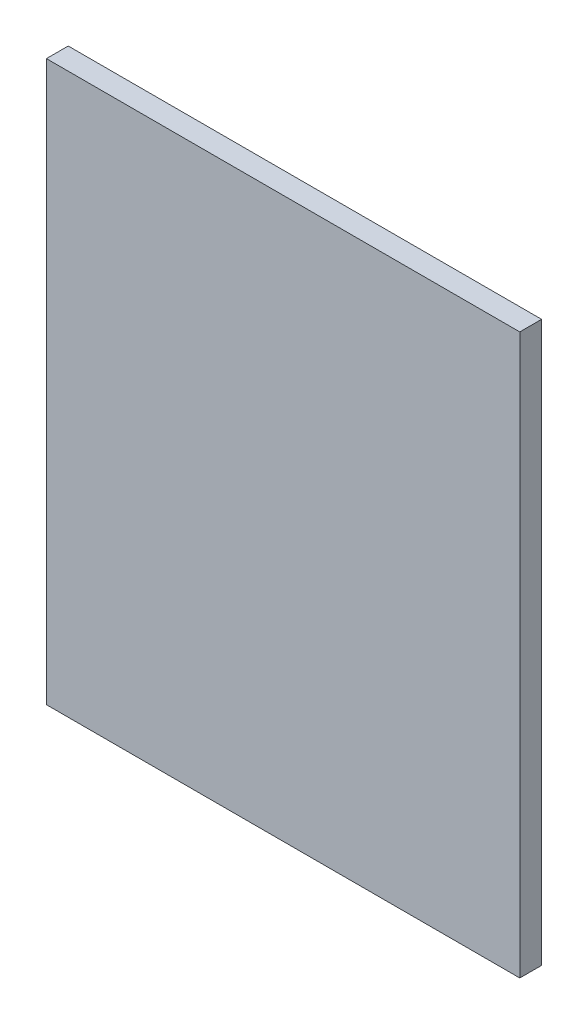
SolidWorks part; units mm, degrees
ref_plane "Front Plane" through (0, 0, 0) normal (0, 0, 1) x (1, 0, 0)
ref_plane "Top Plane" through (0, 0, 0) normal (0, 1, 0) x (1, 0, 0)
ref_plane "Right Plane" through (0, 0, 0) normal (1, 0, 0) x (0, 0, -1)
sketch "Sketch2" plane through (0, 0, 0) normal (0, 0, 1) x (1, 0, 0)
  line L16 (-88.9457, -6.4) -> (-88.9457, -1.9)
  line L17 (-88.9457, -1.9) -> (-93.6457, -1.9)
  line L18 (-93.6457, -1.9) -> (-93.6457, -44.6)
  line L19 (-93.6457, -44.6) -> (-26.1457, -44.6)
  line L20 (-26.1457, -44.6) -> (-26.1457, -1.9)
  line L21 (-26.1457, -1.9) -> (-70.1457, -1.9)
  line L22 (-70.1457, -1.9) -> (-70.1457, -6.4)
  line L23 (-70.1457, -6.4) -> (-88.9457, -6.4)
  line L24 (-88.9457, -6.4) -> (-88.9457, -1.9)
  line L25 (-88.9457, -1.9) -> (-93.6457, -1.9)
  line L26 (-93.6457, -1.9) -> (-93.6457, -44.6)
  line L27 (-93.6457, -44.6) -> (-26.1457, -44.6)
  line L28 (-26.1457, -44.6) -> (-26.1457, -1.9)
  line L29 (-26.1457, -1.9) -> (-70.1457, -1.9)
  line L30 (-70.1457, -1.9) -> (-70.1457, -6.4)
  line L31 (-70.1457, -6.4) -> (-88.9457, -6.4)
  dimension "D1" = 0.4
extrude "Boss-Extrude1" add sketch "Sketch2" along normal blind 2 contours L27 L28 L29 L30 L31 L24 L25 L26
sketch "Sketch3" plane through (0, 0, 2) normal (0, 0, 1) x (1, 0, 0)
  line L8 (-93.6457, -1.9) -> (-93.6457, -44.6)
  line L9 (-93.4457, -2.1) -> (-93.4457, -44.4)
  line L10 (-93.4457, -44.4) -> (-26.3457, -44.4)
  line L11 (-26.3457, -44.4) -> (-26.3457, -2.1)
  line L12 (-26.3457, -2.1) -> (-69.9457, -2.1)
  line L13 (-69.9457, -2.1) -> (-69.9457, -6.6)
  line L14 (-69.9457, -6.6) -> (-89.1457, -6.6)
  line L15 (-89.1457, -6.6) -> (-89.1457, -2.1)
  line L16 (-93.6457, -1.9) -> (-93.6457, -44.6)
  line L17 (-93.6457, -44.6) -> (-26.1457, -44.6)
  line L18 (-26.1457, -44.6) -> (-26.1457, -1.9)
  line L19 (-26.1457, -1.9) -> (-70.1457, -1.9)
  line L20 (-70.1457, -1.9) -> (-70.1457, -6.4)
  line L21 (-70.1457, -6.4) -> (-88.9457, -6.4)
  line L22 (-88.9457, -6.4) -> (-88.9457, -1.9)
  line L23 (-88.9457, -1.9) -> (-93.6457, -1.9)
  line L24 (-93.6457, -1.9) -> (-93.6457, -44.6)
  line L25 (-93.6457, -44.6) -> (-26.1457, -44.6)
  line L26 (-26.1457, -44.6) -> (-26.1457, -1.9)
  line L27 (-26.1457, -1.9) -> (-70.1457, -1.9)
  line L28 (-70.1457, -1.9) -> (-70.1457, -6.4)
  line L29 (-70.1457, -6.4) -> (-88.9457, -6.4)
  line L30 (-88.9457, -6.4) -> (-88.9457, -1.9)
  line L31 (-88.9457, -1.9) -> (-93.6457, -1.9)
  line L32 (-89.1457, -2.1) -> (-93.4457, -2.1)
  line M17 (-93.6457, -1.9) -> (-93.6457, -44.6)
  line M18 (-93.6457, -44.6) -> (-26.1457, -44.6)
  line M19 (-26.1457, -44.6) -> (-26.1457, -1.9)
  line M20 (-26.1457, -1.9) -> (-70.1457, -1.9)
  line M21 (-70.1457, -1.9) -> (-70.1457, -6.4)
  line M22 (-70.1457, -6.4) -> (-88.9457, -6.4)
  line M23 (-88.9457, -6.4) -> (-88.9457, -1.9)
  line M24 (-88.9457, -1.9) -> (-93.6457, -1.9)
  dimension "D1" = 0
  dimension "D2" = 0
  dimension "D3" = 0.2
extrude "Cut-Extrude1" cut sketch "Sketch3" against normal through all contours L32 L15 L14 L13 L12 L11 L10 L9 M24 M17 M18 M19 M20 M21 M22 M23
sketch "Sketch4" plane through (0, 0, 2) normal (0, 0, 1) x (1, 0, 0)
  line L1 (-93.4457, -44.4) -> (-26.3457, -44.4)
  line L2 (-93.4457, -44.4) -> (-93.4457, -53.4)
  line L3 (-93.4457, -53.4) -> (-26.3457, -53.4)
  line L4 (-26.3457, -44.4) -> (-26.3457, -53.4)
  dimension "D1" = 9
extrude "Boss-Extrude2" add sketch "Sketch4" against normal up to surface (2 mm away) up to face at (-69.7207, -13.8, 0)
sketch "Sketch5" plane through (0, 0, 2) normal (0, 0, 1) x (1, 0, 0)
  line L0 (-93.4457, -53.4) -> (-26.3457, -53.4) construction
  line L1 (-93.4457, -2.1) -> (-69.9457, -2.1)
  line L2 (-93.4457, -2.1) -> (-93.4457, -53.4)
  line L3 (-93.4457, -53.4) -> (-69.9457, -53.4)
  line L4 (-69.9457, -2.1) -> (-69.9457, -53.4)
extrude "Cut-Extrude2" cut sketch "Sketch5" against normal blind 10
sketch "Sketch6" plane through (0, 0, 2) normal (0, 0, 1) x (1, 0, 0)
  line L0 (-69.9457, -53.4) -> (-26.3457, -53.4) construction
  line L1 (-69.9457, -2.1) -> (-69.7457, -2.1)
  line L2 (-69.9457, -2.1) -> (-69.9457, -53.4)
  line L3 (-69.9457, -53.4) -> (-69.7457, -53.4)
  line L4 (-69.7457, -2.1) -> (-69.7457, -53.4)
  dimension "D1" = 0.2
extrude "Cut-Extrude3" cut sketch "Sketch6" against normal blind 10
